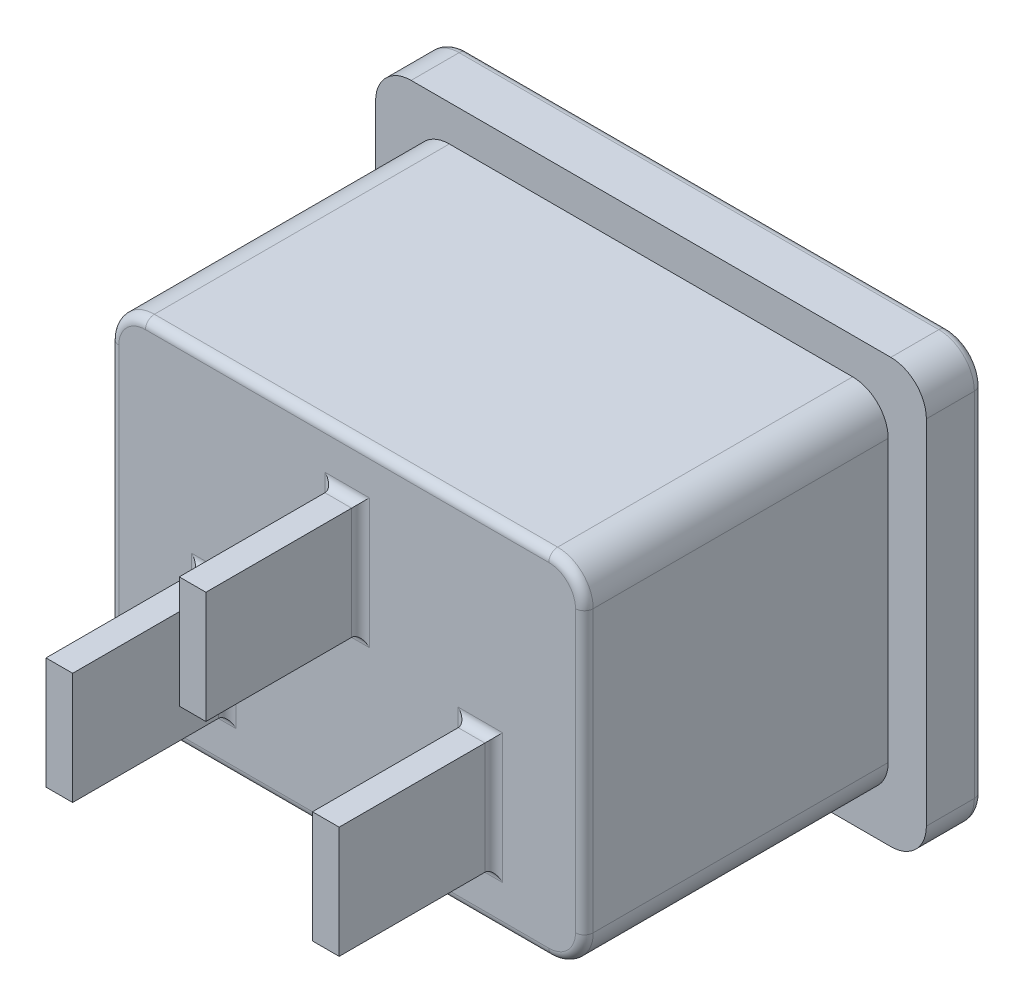
SolidWorks part; units mm, degrees
material "Nylon 101"
ref_plane "Plan de face" through (0, 0, 0) normal (0, 0, 1) x (1, 0, 0)
ref_plane "Plan de dessus" through (0, 0, 0) normal (0, 1, 0) x (1, 0, 0)
ref_plane "Plan de droite" through (0, 0, 0) normal (1, 0, 0) x (0, 0, -1)
sketch "Esquisse1" plane through (0, 0, 0) normal (0, 0, 1) x (1, 0, 0)
  line L1 (-15.5, 11.925) -> (15.5, 11.925)
  line L2 (-15.5, 11.925) -> (-15.5, -11.925)
  line L3 (-15.5, -11.925) -> (15.5, -11.925)
  line L4 (15.5, 11.925) -> (15.5, -11.925)
  line L5 (-15.5, 11.925) -> (15.5, -11.925) construction
  line L6 (-15.5, -11.925) -> (15.5, 11.925) construction
  point P0 (0, 0)
  dimension "D1" = 23.85
  dimension "D2" = 31
extrude "Boss.-Extru.1" add sketch "Esquisse1" along normal blind 3.2
sketch "Esquisse2" plane through (0, 0, 0) normal (0, 0, -1) x (-1, 0, 0)
  line L1 (-13.35, 9.9) -> (13.35, 9.9)
  line L2 (-13.35, 9.9) -> (-13.35, -9.9)
  line L3 (-13.35, -9.9) -> (13.35, -9.9)
  line L4 (13.35, 9.9) -> (13.35, -9.9)
  line L5 (-13.35, 9.9) -> (13.35, -9.9) construction
  line L6 (-13.35, -9.9) -> (13.35, 9.9) construction
  point P0 (0, 0)
  dimension "D1" = 19.8
  dimension "D2" = 26.7
extrude "Boss.-Extru.2" add sketch "Esquisse2" against normal blind 20.3
sketch "Esquisse3" plane through (0, 0, 0) normal (0, 0, -1) x (-1, 0, 0)
  line L1 (-12, 8) -> (12, 8)
  line L2 (-12, 8) -> (-12, -8)
  line L3 (-12, -8) -> (12, -8)
  line L4 (12, 8) -> (12, -8)
  line L5 (-12, 8) -> (12, -8) construction
  line L6 (-12, -8) -> (12, 8) construction
  point P0 (0, 0)
  dimension "D1" = 16
  dimension "D2" = 24
extrude "Enlèv. mat.-Extru.1" cut sketch "Esquisse3" against normal blind 17
chamfer "Chanfrein1" distance 5 angle 45 2 edges at (12, 8, 8.5) (-12, 8, 8.5)
sketch "Esquisse4" plane through (0, 0, 17) normal (0, 0, -1) x (-1, 0, 0)
  line L0 (7, 8) -> (-7, 8) construction
  line L1 (-0.75, 7) -> (0.75, 7)
  line L2 (-0.75, 7) -> (-0.75, 0.7)
  line L3 (-0.75, 0.7) -> (0.75, 0.7)
  line L4 (0.75, 7) -> (0.75, 0.7)
  line L5 (-0.75, 7) -> (0.75, 0.7) construction
  line L6 (-0.75, 0.7) -> (0.75, 7) construction
  line L7 (0, 0) -> (0, -6.8789) construction
  line L8 (-8.25, -0.7) -> (-6.75, -0.7)
  line L9 (-8.25, -0.7) -> (-8.25, -7)
  line L10 (-8.25, -7) -> (-6.75, -7)
  line L11 (-6.75, -0.7) -> (-6.75, -7)
  line L12 (-8.25, -0.7) -> (-6.75, -7) construction
  line L13 (-8.25, -7) -> (-6.75, -0.7) construction
  line L14 (6.75, -0.7) -> (8.25, -0.7)
  line L15 (6.75, -0.7) -> (6.75, -7)
  line L16 (6.75, -7) -> (8.25, -7)
  line L17 (8.25, -0.7) -> (8.25, -7)
  line L18 (6.75, -0.7) -> (8.25, -7) construction
  line L19 (6.75, -7) -> (8.25, -0.7) construction
  line L20 (-12, -8) -> (12, -8) construction
  point P0 (0, 3.85)
  point P8 (-7.5, -3.85)
  point P13 (7.5, -3.85)
  dimension "D1" = 6.3
  dimension "D2" = 1.5
  dimension "D3" = 1
  dimension "D4" = 6.3
  dimension "D5" = 1.5
  dimension "D6" = 6.3
  dimension "D7" = 1.5
  dimension "D8" = 1
  dimension "D9" = 15
extrude "Boss.-Extru.3" add sketch "Esquisse4" along normal blind 16 and the other way offset from surface (12 mm away) 29 other way up to face at (0, 1, 0)
fillet "Congé1" radius 2 14 edges at (15.5, -11.925, 1.6) (-15.5, -11.925, 1.6) (-15.5, 11.925, 1.6) (15.5, 11.925, 1.6) (13.35, -9.9, 11.75) (-13.35, -9.9, 11.75) (-13.35, 9.9, 11.75) (13.35, 9.9, 11.75) (-12, -8, 8.5) (-12, 3, 8.5) (-7, 8, 8.5) (7, 8, 8.5) (12, -8, 8.5) (12, 3, 8.5)
fillet "Congé2" radius 0.5 40 edges at (-12.7642, -9.3142, 20.3) (-13.35, 0, 20.3) (-12.7642, 9.3142, 20.3) (0, 9.9, 20.3) (12.7642, 9.3142, 20.3) (13.35, 0, 20.3) (12.7642, -9.3142, 20.3) (0, -9.9, 20.3) (0, 0.7, 20.3) (0.75, 3.85, 20.3) (0, 7, 20.3) (-0.75, 3.85, 20.3) (7.5, -7, 20.3) (8.25, -3.85, 20.3) (7.5, -0.7, 20.3) (6.75, -3.85, 20.3) (-7.5, -7, 20.3) (-6.75, -3.85, 20.3) (-7.5, -0.7, 20.3) (-8.25, -3.85, 20.3) (14.9142, 11.3392, 0) (0, 11.925, 0) (-14.9142, 11.3392, 0) (-15.5, 0, 0) (-14.9142, -11.3392, 0) (0, -11.925, 0) (14.9142, -11.3392, 0) (15.5, 0, 0) (6.9369, 7.8478, 0) (9.5, 5.5, 0) (11.8478, 2.9369, 0) (12, -1.9142, 0) (11.4142, -7.4142, 0) (0, -8, 0) (-11.4142, -7.4142, 0) (-12, -1.9142, 0) (-11.8478, 2.9369, 0) (-9.5, 5.5, 0) (-6.9369, 7.8478, 0) (0, 8, 0)
